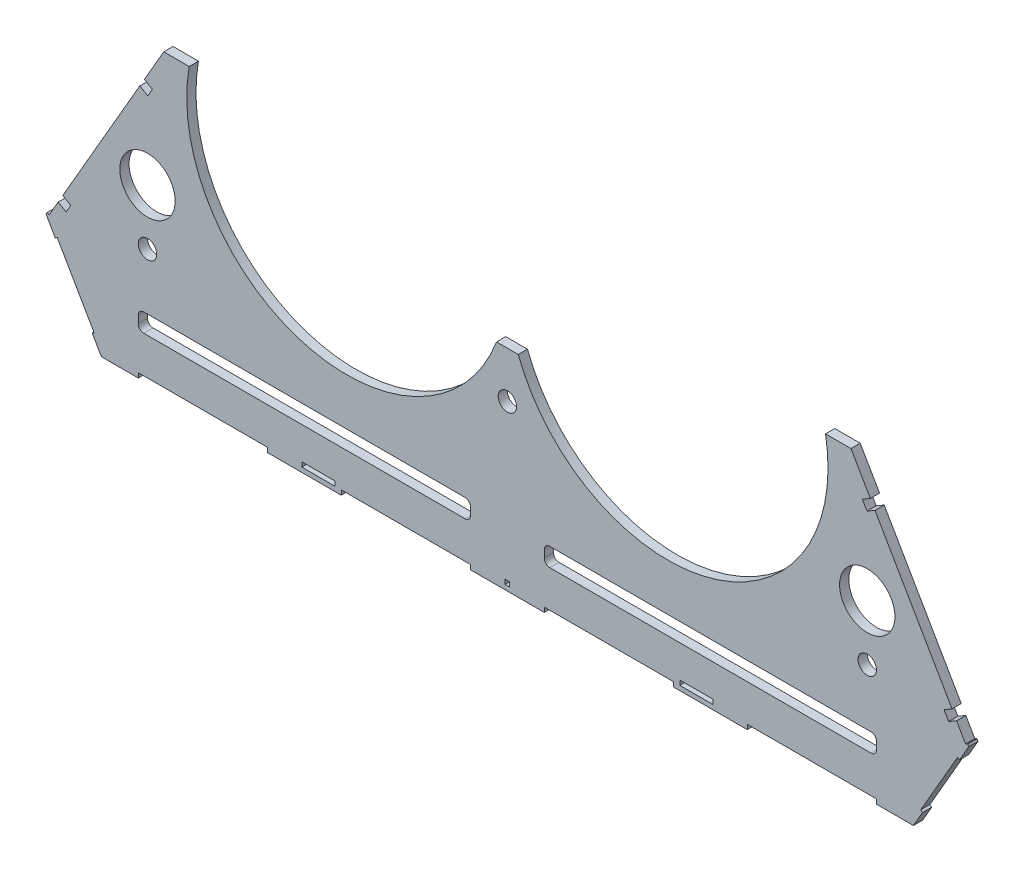
SolidWorks part; units mm, degrees
material "Teak"
ref_plane "Front Plane" through (0, 0, 0) normal (0, 0, 1) x (1, 0, 0)
ref_plane "Top Plane" through (0, 0, 0) normal (0, 1, 0) x (1, 0, 0)
ref_plane "Right Plane" through (0, 0, 0) normal (1, 0, 0) x (0, 0, -1)
sketch "Sketch3" plane through (0, 0, 0) normal (0, 0, 1) x (1, 0, 0)
  line L0 (-279.4, 0) -> (279.4, 0)
  line L5 (279.4, 0) -> (317.5, 65.9911)
  line L14 (317.5, 65.9911) -> (172.2913, 317.5)
  line L15 (172.2913, 317.5) -> (-172.2913, 317.5)
  line L17 (-317.5, 65.9911) -> (-172.2913, 317.5)
  line L18 (-279.4, 0) -> (-317.5, 65.9911)
  line L21 (-7.4804, 144.78) -> (7.4804, 144.78)
  line L22 (218.9308, 203.2) -> (238.2824, 203.2)
  line L23 (-218.9308, 203.2) -> (-238.2824, 203.2)
  arc A2 (7.4804, 144.78) -> (110.49, 73.66) centre (110.49, 183.8191) ccw
  arc A3 (-7.4804, 144.78) -> (-110.49, 73.66) centre (-110.49, 183.8191) cw
  arc A4 (218.9308, 203.2) -> (110.49, 73.66) centre (110.49, 183.8191) cw
  arc A5 (-218.9308, 203.2) -> (-110.49, 73.66) centre (-110.49, 183.8191) ccw
  point P0 (0, 0)
  point P9 (0, 144.78)
  point P11 (0, 317.5)
  dimension "D10" = 60
  dimension "D11" = 203.2
  dimension "D12" = 73.66
  dimension "D9" = 110.1591
  dimension "D13" = 220.98
  dimension "D14" = 110.1591
  dimension "D1" = 558.8
  dimension "D2" = 76.2
  dimension "D3" = 317.5
  dimension "D4" = 60
  dimension "D5" = 144.78
  dimension "D6" = 60
  dimension "D7" = 60
  dimension "D8" = 76.2
extrude "Boss-Extrude1" add sketch "Sketch3" along normal blind 6.35
sketch "Sketch4" plane through (0, 0, 6.35) normal (0, 0, 1) x (1, 0, 0)
  line L0 (-279.4, 0) -> (279.4, 0) construction
  line L1 (-254, 0) -> (-165.1, 0)
  line L2 (-254, 0) -> (-254, 3.175)
  line L3 (-254, 3.175) -> (-165.1, 3.175)
  line L4 (-165.1, 0) -> (-165.1, 3.175)
  line L5 (-114.3, 3.175) -> (-25.4, 3.175)
  line L6 (-25.4, 0) -> (-25.4, 3.175)
  line L7 (-114.3, 0) -> (-25.4, 0)
  line L8 (-114.3, 0) -> (-114.3, 3.175)
  line L9 (25.4, 3.175) -> (114.3, 3.175)
  line L10 (114.3, 0) -> (114.3, 3.175)
  line L11 (25.4, 0) -> (114.3, 0)
  line L12 (25.4, 0) -> (25.4, 3.175)
  line L13 (165.1, 3.175) -> (254, 3.175)
  line L14 (254, 0) -> (254, 3.175)
  line L15 (165.1, 0) -> (254, 0)
  line L16 (165.1, 0) -> (165.1, 3.175)
  dimension "D1" = 25.4
  dimension "D2" = 3.175
  dimension "D3" = 88.9
  dimension "D5" = 50.8
  dimension "D4" = 4
extrude "Cut-Extrude1" cut sketch "Sketch4" against normal through all
sketch "Sketch5" plane through (0, 0, 6.35) normal (0, 0, 1) x (1, 0, 0)
  line L0 (-311.15, 54.9926) -> (-309.7752, 55.7864)
  line L1 (-279.4, 0) -> (-317.5, 65.9911) construction
  line L2 (-309.7752, 55.7864) -> (-284.3752, 11.7923)
  line L3 (-284.3752, 11.7923) -> (-285.75, 10.9985)
  line L4 (-285.75, 10.9985) -> (-311.15, 54.9926)
  line L5 (0, -1000) -> (0, 49000) construction
  line L6 (285.75, 10.9985) -> (311.15, 54.9926)
  line L7 (284.3752, 11.7923) -> (285.75, 10.9985)
  line L8 (309.7752, 55.7864) -> (284.3752, 11.7923)
  line L9 (311.15, 54.9926) -> (309.7752, 55.7864)
  dimension "D1" = 1.5875
  dimension "D2" = 12.7
  dimension "D3" = 12.7
extrude "Cut-Extrude2" cut sketch "Sketch5" against normal through all
sketch "Sketch8" plane through (0, 0, 6.35) normal (0, 0, 1) x (1, 0, 0)
  line L3 (-315.3632, 66.5172) -> (-236.4493, 203.2)
  line L5 (-316.738, 67.311) -> (-315.3632, 66.5172)
  line L6 (-317.5, 65.9911) -> (-238.2824, 203.2) construction
  line L11 (0, -853.8361) -> (0, 49146.1639) construction
  line L12 (-7.4804, 144.78) -> (7.4804, 144.78) construction
  line L17 (-218.9308, 203.2) -> (-238.2824, 203.2) construction
  line L18 (-236.4493, 203.2) -> (-238.2824, 203.2)
  line L19 (-238.2824, 203.2) -> (-316.738, 67.311)
  line L20 (316.738, 67.311) -> (315.3632, 66.5172)
  line L21 (238.2824, 203.2) -> (316.738, 67.311)
  line L22 (236.4493, 203.2) -> (238.2824, 203.2)
  line L23 (315.3632, 66.5172) -> (236.4493, 203.2)
  point P16 (0, 144.78)
  dimension "D1" = 1.524
  dimension "D2" = 1.5875
extrude "Cut-Extrude5" cut sketch "Sketch8" against normal through all
sketch "Sketch9" plane through (0, 0, 6.35) normal (0, 0, 1) x (1, 0, 0)
  line L0 (-252.9593, 174.6038) -> (-247.4601, 171.4288)
  line L1 (-315.3632, 66.5172) -> (-236.4493, 203.2) construction
  line L2 (-247.4601, 171.4288) -> (-244.2851, 176.9281)
  line L3 (-244.2851, 176.9281) -> (-249.7843, 180.1031)
  line L4 (-249.7843, 180.1031) -> (-252.9593, 174.6038)
  line L5 (0, -853.8361) -> (0, 49146.1639) construction
  line L6 (-7.4804, 144.78) -> (7.4804, 144.78) construction
  line L7 (249.7843, 180.1031) -> (252.9593, 174.6038)
  line L8 (252.9593, 174.6038) -> (247.4601, 171.4288)
  line L9 (244.2851, 176.9281) -> (249.7843, 180.1031)
  line L10 (247.4601, 171.4288) -> (244.2851, 176.9281)
  line L11 (-303.6409, 74.1208) -> (-300.4659, 79.62)
  line L12 (-300.4659, 79.62) -> (-305.9652, 82.795)
  line L13 (-309.1402, 77.2958) -> (-303.6409, 74.1208)
  line L14 (-305.9652, 82.795) -> (-309.1402, 77.2958)
  line L15 (305.9652, 82.795) -> (309.1402, 77.2958)
  line L16 (309.1402, 77.2958) -> (303.6409, 74.1208)
  line L17 (300.4659, 79.62) -> (305.9652, 82.795)
  line L18 (303.6409, 74.1208) -> (300.4659, 79.62)
  point P12 (0, 144.78)
  dimension "D1" = 6.35
  dimension "D2" = 6.35
  dimension "D3" = 26.67
  dimension "D5" = 12.446
  dimension "D4" = 2
extrude "Cut-Extrude6" cut sketch "Sketch9" against normal through all
sketch "Sketch10" [suppressed] plane through (0, 0, 6.35) normal (0, 0, 1) x (1, 0, 0)
  line L0 (1.5875, 3.175) -> (1.5875, 6.35)
  line L1 (-141.2875, 3.175) -> (-138.1125, 3.175)
  line L2 (-141.2875, 3.175) -> (-141.2875, 6.35)
  line L3 (-141.2875, 6.35) -> (-138.1125, 6.35)
  line L4 (-138.1125, 3.175) -> (-138.1125, 6.35)
  line L5 (-165.1, 0) -> (-165.1, 3.175) construction
  line L6 (-25.4, 3.175) -> (-114.3, 3.175) construction
  line L7 (-1.5875, 3.175) -> (-1.5875, 6.35)
  line L8 (-1.5875, 3.175) -> (1.5875, 3.175)
  line L9 (-1.5875, 6.35) -> (1.5875, 6.35)
  line L10 (141.2875, 3.175) -> (141.2875, 6.35)
  line L11 (138.1125, 3.175) -> (138.1125, 6.35)
  line L12 (138.1125, 3.175) -> (141.2875, 3.175)
  line L13 (138.1125, 6.35) -> (141.2875, 6.35)
  point P6 (-139.7, 3.175)
  point P9 (-165.1, 1.5875)
  dimension "D1" = 25.4
  dimension "D2" = 3.175
  dimension "D3" = 3.175
  dimension "D4" = 0
  dimension "D5" = 3
extrude "Cut-Extrude7" [suppressed] cut sketch "Sketch10" against normal through all
sketch "Sketch12" plane through (0, 0, 6.35) normal (0, 0, 1) x (1, 0, 0)
  line L0 (-25.4, 3.175) -> (-114.3, 3.175) construction
  line L1 (-141.478, 3.175) -> (-118.618, 3.175)
  line L2 (-141.478, 3.175) -> (-141.478, 6.35)
  line L3 (-141.478, 6.35) -> (-118.618, 6.35)
  line L4 (-118.618, 3.175) -> (-118.618, 6.35)
  line L5 (-25.4, 0) -> (-25.4, 3.175) construction
  line L6 (0, -3.4925) -> (0, 3.4925) construction
  line L7 (118.618, 3.175) -> (118.618, 6.35)
  line L8 (141.478, 6.35) -> (118.618, 6.35)
  line L9 (141.478, 3.175) -> (141.478, 6.35)
  line L10 (141.478, 3.175) -> (118.618, 3.175)
  line L11 (-1.5875, 3.175) -> (1.5875, 3.175)
  line L12 (-1.5875, 3.175) -> (-1.5875, 6.35)
  line L13 (-1.5875, 6.35) -> (1.5875, 6.35)
  line L14 (1.5875, 3.175) -> (1.5875, 6.35)
  point P18 (0, 6.35)
  dimension "D1" = 160.782
  dimension "D2" = 3.175
  dimension "D3" = 22.86
  dimension "D4" = 3.175
  dimension "D5" = 3.175
  dimension "D6" = 25.4
extrude "Cut-Extrude8" cut sketch "Sketch12" against normal through all
sketch "Sketch13" plane through (0, 0, 0) normal (0, 0, -1) x (-1, 0, 0)
  line L0 (0, 0) -> (0, 144.78) construction
  line L1 (7.4804, 144.78) -> (-7.4804, 144.78) construction
  line L2 (-1224.7311, 73.66) -> (48775.2689, 73.66) construction
  circle A1 centre (-247.65, 80.01) radius 6.35
  circle A2 centre (247.65, 80.01) radius 6.35
  arc A4 (-218.9308, 203.2) -> (-7.4804, 144.78) centre (-110.49, 183.8191) ccw construction
  dimension "D1" = 12.7
  dimension "D2" = 247.65
extrude "nylon bolt cut" cut sketch "Sketch13" against normal up to next
sketch "Sketch14" plane through (0, 0, 6.35) normal (0, 0, 1) x (1, 0, 0)
  line L0 (-247.65, 80.01) -> (-247.65, 123.2652) construction
  line L1 (0, 144.78) -> (0, -2.5224) construction
  line L2 (-7.4804, 144.78) -> (7.4804, 144.78) construction
  circle A0 centre (-247.65, 118.11) radius 19.05
  circle A1 centre (-247.65, 80.01) radius 6.35 construction
  circle A2 centre (247.65, 118.11) radius 19.05
  dimension "D1" = 38.1
  dimension "D2" = 38.1
extrude "Cut-Extrude9" cut sketch "Sketch14" against normal through all
sketch "Sketch15" plane through (0, 0, 6.35) normal (0, 0, 1) x (1, 0, 0)
  line L0 (-7.4804, 144.78) -> (7.4804, 144.78) construction
  circle A0 centre (0, 113.03) radius 6.35
  dimension "D1" = 12.7
  dimension "D2" = 31.75
extrude "static payload bolt" cut sketch "Sketch15" against normal through all
sketch "Sketch16" plane through (0, 0, 6.35) normal (0, 0, 1) x (1, 0, 0)
  line L0 (-25.4, 3.175) -> (-114.3, 3.175) construction
  line L1 (-250.19, 41.275) -> (-29.21, 41.275)
  line L2 (-254, 37.465) -> (-254, 32.385)
  line L3 (-250.19, 28.575) -> (-29.21, 28.575)
  line L4 (254, 37.465) -> (254, 32.385)
  line L5 (-25.4, 0) -> (25.4, 0) construction
  line L6 (-25.4, 32.385) -> (-25.4, 37.465)
  line L7 (25.4, 32.385) -> (25.4, 37.465)
  line L8 (29.21, 28.575) -> (250.19, 28.575)
  line L9 (29.21, 41.275) -> (250.19, 41.275)
  arc A0 (250.19, 41.275) -> (254, 37.465) centre (250.19, 37.465) cw
  arc A1 (250.19, 28.575) -> (254, 32.385) centre (250.19, 32.385) ccw
  arc A2 (25.4, 32.385) -> (29.21, 28.575) centre (29.21, 32.385) ccw
  arc A3 (25.4, 37.465) -> (29.21, 41.275) centre (29.21, 37.465) cw
  arc A4 (-25.4, 37.465) -> (-29.21, 41.275) centre (-29.21, 37.465) ccw
  arc A5 (-25.4, 32.385) -> (-29.21, 28.575) centre (-29.21, 32.385) cw
  arc A6 (-254, 32.385) -> (-250.19, 28.575) centre (-250.19, 32.385) ccw
  arc A7 (-250.19, 41.275) -> (-254, 37.465) centre (-250.19, 37.465) ccw
  point P8 (0, 0)
  point P15 (254, 41.275)
  point P21 (25.4, 28.575)
  point P24 (25.4, 41.275)
  point P31 (-254, 28.575)
  point P34 (-254, 41.275)
  dimension "D7" = 3.81
  dimension "D1" = 12.7
  dimension "D2" = 508
  dimension "D3" = 25.4
  dimension "D4" = 50.8
  dimension "D5" = 25.4
  dimension "D6" = 25.4
extrude "Cut-Extrude10" cut sketch "Sketch16" against normal through all
